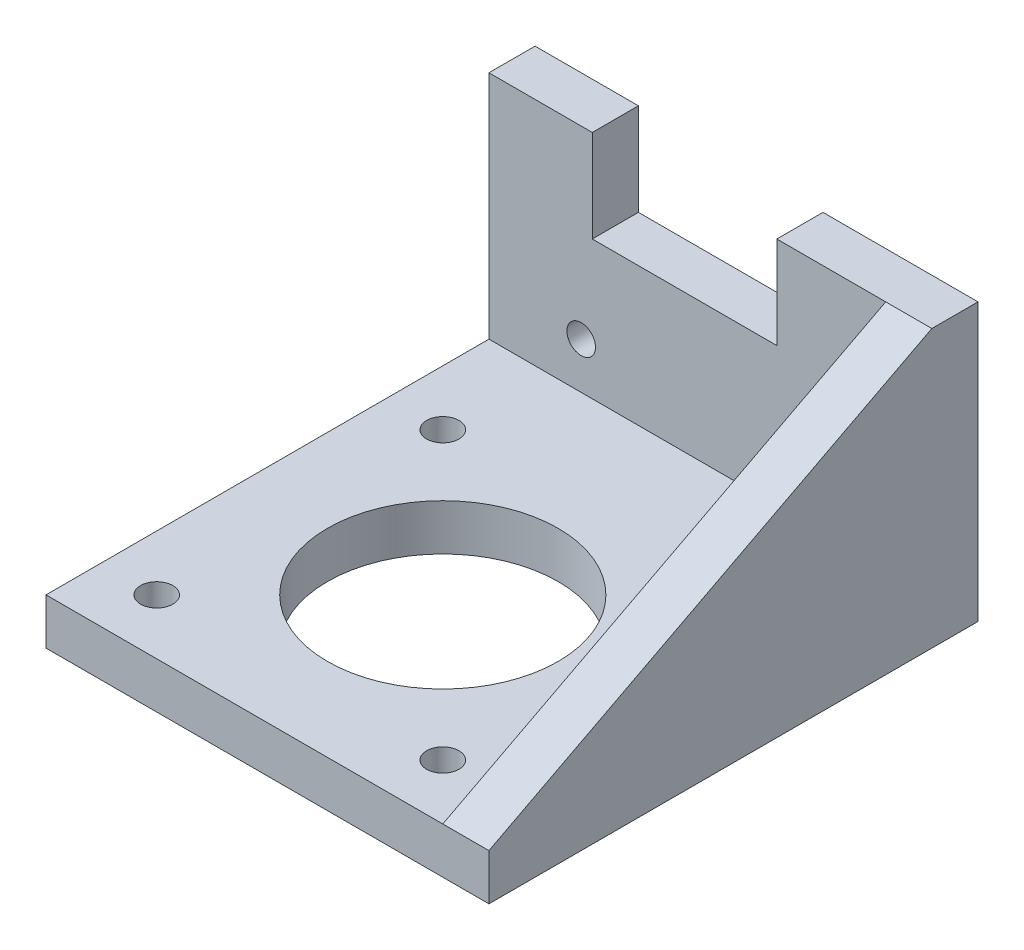
SolidWorks part; units mm, degrees
ref_plane "前视基准面" through (0, 0, 0) normal (0, 0, 1) x (1, 0, 0)
ref_plane "上视基准面" through (0, 0, 0) normal (0, 1, 0) x (1, 0, 0)
ref_plane "右视基准面" through (0, 0, 0) normal (1, 0, 0) x (0, 0, -1)
sketch "草图1" plane through (0, 0, 0) normal (0, 1, 0) x (1, 0, 0)
  line L1 (-35.8997, 33.2122) -> (7.1003, 33.2122)
  line L2 (-35.8997, 33.2122) -> (-35.8997, -9.7878)
  line L3 (-35.8997, -9.7878) -> (7.1003, -9.7878)
  line L4 (7.1003, 33.2122) -> (7.1003, -9.7878)
  line L5 (-14.3997, -9.7878) -> (-14.3997, 33.2122) construction
  line L6 (-35.8997, 11.7122) -> (7.1003, 11.7122) construction
  line L7 (-29.8997, 27.2122) -> (1.1003, 27.2122) construction
  line L8 (-29.8997, 27.2122) -> (-29.8997, -3.7878) construction
  line L9 (-29.8997, -3.7878) -> (1.1003, -3.7878) construction
  line L10 (1.1003, 27.2122) -> (1.1003, -3.7878) construction
  line L11 (-14.3997, -3.7878) -> (-14.3997, 27.2122) construction
  line L12 (-29.8997, 11.7122) -> (1.1003, 11.7122) construction
  circle A0 centre (1.1003, 27.2122) radius 1.75
  circle A1 centre (-29.8997, 27.2122) radius 1.75
  circle A2 centre (-29.8997, -3.7878) radius 1.75
  circle A3 centre (1.1003, -3.7878) radius 1.75
  circle A4 centre (-14.3997, 11.7122) radius 12.5
  point P0 (-14.3997, 11.7122)
  point P4 (-14.3997, 11.7122)
  dimension "D4" = 3.5
  dimension "D5" = 25
  dimension "D1" = 43
  dimension "D2" = 43
  dimension "D3" = 31
extrude "凸台-拉伸1" add sketch "草图1" along normal blind 5
sketch "草图3" plane through (0, 0, -33.2122) normal (0, 0, -1) x (-1, 0, 0)
  line L4 (-7.1003, 0) -> (35.8997, 0)
  line L5 (35.8997, 0) -> (35.8997, 5)
  line L6 (35.8997, 5) -> (-7.1003, 5)
  line L7 (-7.1003, 5) -> (-7.1003, 0)
  line L8 (-7.1003, 0) -> (35.8997, 0)
  line L9 (35.8997, 0) -> (35.8997, 5)
  line L10 (35.8997, 5) -> (-7.1003, 5)
  line L11 (-7.1003, 5) -> (-7.1003, 0)
  dimension "D1" = 0
extrude "凸台-拉伸2" add sketch "草图3" along normal blind 5
sketch "草图4" plane through (0, 0, -38.2122) normal (0, 0, -1) x (-1, 0, 0)
  line L1 (35.8997, 0) -> (-7.1003, 0)
  line L2 (35.8997, 0) -> (35.8997, 30)
  line L3 (35.8997, 30) -> (-7.1003, 30)
  line L4 (-7.1003, 0) -> (-7.1003, 30)
  line L5 (35.8997, 0) -> (-7.1003, 30) construction
  line L6 (35.8997, 30) -> (-7.1003, 0) construction
  point P4 (14.3997, 15)
  dimension "D1" = 30
extrude "凸台-拉伸3" add sketch "草图4" along normal blind 5
sketch "草图5" plane through (0, 0, -38.2122) normal (0, 0, 1) x (1, 0, 0)
  line L0 (7.8515, 13.6) -> (7.8515, 6.4) construction
  line L1 (195.9052, 13.6) -> (-204.0948, 13.6) construction
  line L2 (195.9052, 6.4) -> (-204.0948, 6.4) construction
  line L3 (7.1003, 10) -> (-35.8997, 10) construction
  line L4 (7.1003, 30) -> (7.1003, 5) construction
  line L5 (-35.8997, 5) -> (-35.8997, 30) construction
  circle A0 centre (-0.8997, 10) radius 1.55
  circle A1 centre (-25.8997, 10) radius 1.55
  dimension "D1" = 3.1
  dimension "D2" = 3.1
  dimension "D3" = 25
  dimension "D4" = 8
extrude "切除-拉伸1" cut sketch "草图5" against normal through all
sketch "草图6" plane through (7.1003, 0, 0) normal (1, 0, 0) x (0, 0, -1)
  line L1 (-9.7878, 0) -> (-9.7878, 5)
  line L2 (-9.7878, 5) -> (38.2122, 30)
  line L3 (38.2122, 30) -> (43.2122, 30)
  line L4 (43.2122, 30) -> (43.2122, 0)
  line L5 (43.2122, 0) -> (-9.7878, 0)
extrude "凸台-拉伸4" add sketch "草图6" along normal blind 5
sketch "草图7" plane through (0, 30, 0) normal (0, 1, 0) x (1, 0, 0)
  line L0 (-4.6997, 38.2122) -> (-4.6997, 43.2122)
  line L1 (-35.8997, 38.2122) -> (7.1003, 38.2122) construction
  line L2 (-35.8997, 43.2122) -> (12.1003, 43.2122) construction
  line L3 (-4.6997, 43.2122) -> (-24.6997, 43.2122)
  line L4 (-24.6997, 43.2122) -> (-24.6997, 38.2122)
  line L5 (-24.6997, 38.2122) -> (-4.6997, 38.2122)
  line L6 (-35.8997, 43.2122) -> (-35.8997, 38.2122) construction
  dimension "D1" = 20
  dimension "D2" = 11.2
extrude "切除-拉伸2" cut sketch "草图7" against normal blind 10
